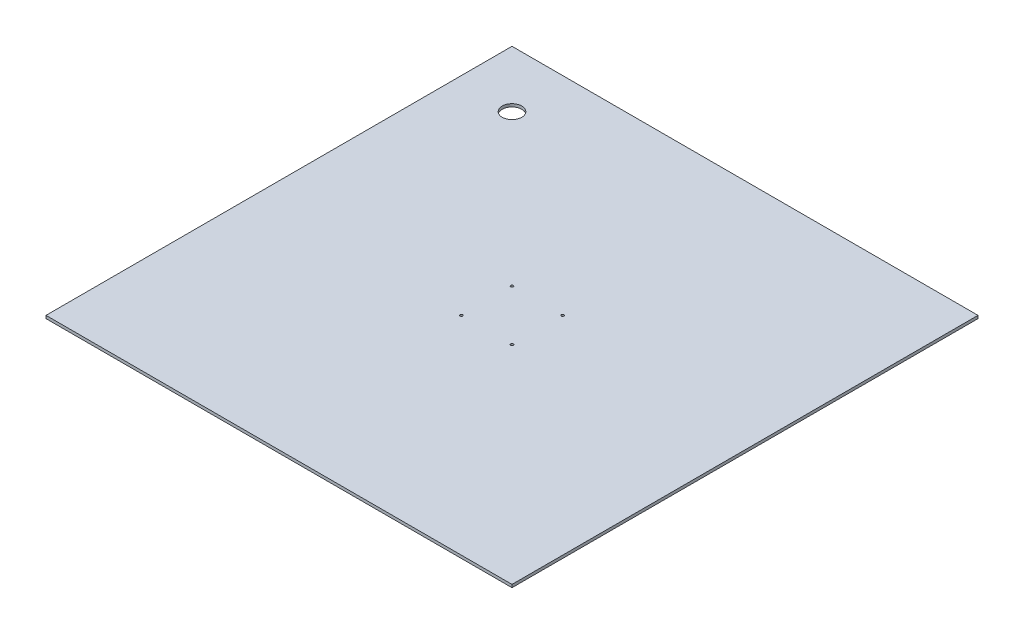
SolidWorks part; units mm, degrees
material "Acrylic (Medium-high impact)"
ref_plane "Front Plane" through (0, 0, 0) normal (0, 0, 1) x (1, 0, 0)
ref_plane "Top Plane" through (0, 0, 0) normal (0, 1, 0) x (1, 0, 0)
ref_plane "Right Plane" through (0, 0, 0) normal (1, 0, 0) x (0, 0, -1)
sketch "Sketch1" plane through (0, 0, 0) normal (0, 1, 0) x (1, 0, 0)
  line L1 (-257.175, 257.175) -> (257.175, 257.175)
  line L2 (-257.175, 257.175) -> (-257.175, -257.175)
  line L3 (-257.175, -257.175) -> (257.175, -257.175)
  line L4 (257.175, 257.175) -> (257.175, -257.175)
  line L5 (-257.175, 257.175) -> (257.175, -257.175) construction
  line L6 (-257.175, -257.175) -> (257.175, 257.175) construction
  circle A1 centre (-194.7224, 194.7224) radius 10.795
  point P0 (0, 0)
  dimension "D3" = 21.59
  dimension "D4" = 62.4526
  dimension "D1" = 514.35
  dimension "D2" = 514.35
extrude "Boss-Extrude1" add sketch "Sketch1" along normal blind 3.175
sketch "Sketch2" plane through (0, 3.175, 0) normal (0, 1, 0) x (1, 0, 0)
  line L5 (0, -38.1) -> (0, 38.1) construction
  line L6 (38.1, 0) -> (-38.1, 0) construction
  circle A0 centre (-27.94, 27.94) radius 1.45
  circle A1 centre (27.94, 27.94) radius 1.45
  circle A2 centre (27.94, -27.94) radius 1.45
  circle A3 centre (-27.94, -27.94) radius 1.45
  point P0 (0, 0)
  dimension "D5" = 2.9
  dimension "D1" = 27.94
  dimension "D2" = 27.94
extrude "Cut-Extrude1" cut sketch "Sketch2" against normal through all
